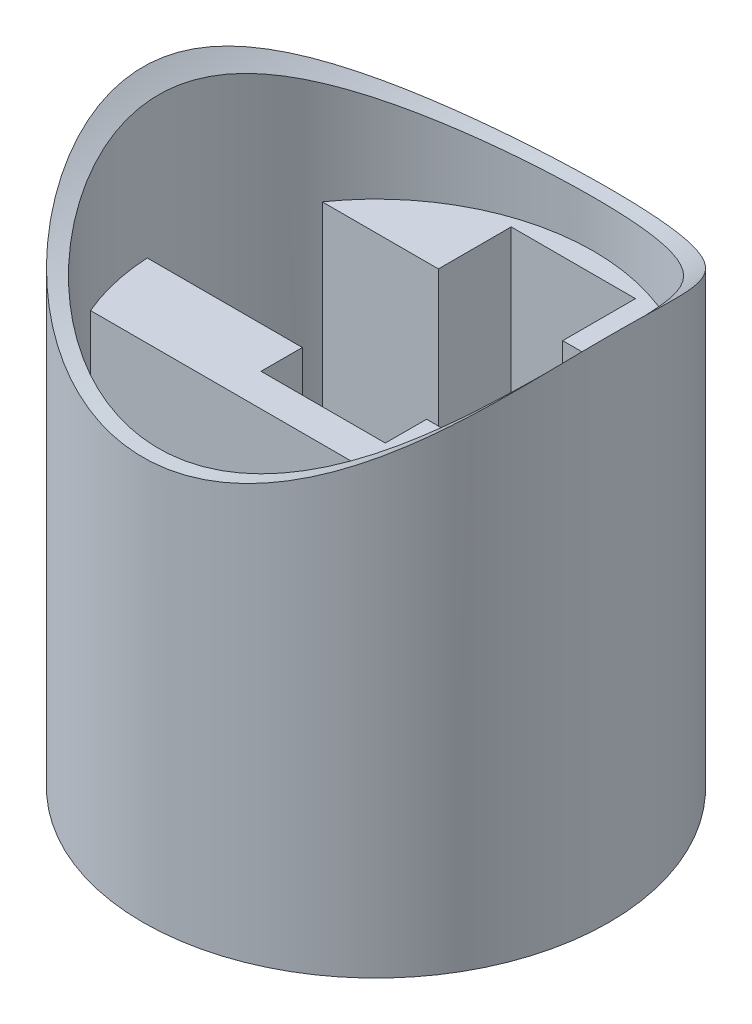
SolidWorks part; units mm, degrees
ref_plane "Front Plane" through (0, 0, 0) normal (0, 0, 1) x (1, 0, 0)
ref_plane "Top Plane" through (0, 0, 0) normal (0, 1, 0) x (1, 0, 0)
ref_plane "Right Plane" through (0, 0, 0) normal (1, 0, 0) x (0, 0, -1)
sketch "Sketch2" plane through (0, 0, 0) normal (0, 1, 0) x (1, 0, 0)
  line L0 (-28.6937, 20.0417) -> (-10, 20.0417)
  line L1 (-10, 31.75) -> (10, 31.75)
  line L2 (-10, 31.75) -> (-10, -8.5)
  line L3 (-10, -8.5) -> (10, -8.5)
  line L4 (10, 31.75) -> (10, -8.5)
  line L5 (-34.9505, -1.8615) -> (-10, -1.8615)
  line L6 (-32.1853, -13.7516) -> (32.1853, -13.7516)
  line L7 (0, -55) -> (0, 55) construction
  line L8 (34.9505, -1.8615) -> (10, -1.8615)
  line L9 (28.6937, 20.0417) -> (10, 20.0417)
  circle A0 centre (0, 0) radius 37.5
  circle A1 centre (0, 0) radius 35
  point P14 (0, 0)
  point P18 (0, -13.7516)
  dimension "D1" = 75
  dimension "D6" = 70
  dimension "D2" = 40.25
  dimension "D3" = 20
  dimension "D4" = 10
  dimension "D5" = 8.5
  dimension "D7" = 20.0417
  dimension "D8" = 1.8615
  dimension "D9" = 5.2516
extrude "Boss-Extrude2" add sketch "Sketch2" along normal blind 37.3 contours A0 A1 | L9 A1 L0 L2 L1 L4 | L6 A1 L8 L4 L3 L2 L5
sketch "Sketch3" plane through (0, 0, 0) normal (0, -1, 0) x (1, 0, 0)
  circle A0 centre (0, 0) radius 37.5
extrude "Boss-Extrude3" add sketch "Sketch3" along normal blind 20
sketch "Sketch4" plane through (0, 37.3, 0) normal (0, 1, 0) x (1, 0, 0)
  circle A0 centre (0, 0) radius 37.5
  circle A1 centre (0, 0) radius 35
extrude "Boss-Extrude4" add sketch "Sketch4" along normal blind 40
sketch "Sketch5" plane through (0, 0, 0) normal (0, 0, 1) x (1, 0, 0)
  line L1 (35, 77.3) -> (-35, 77.3) construction
  circle A0 centre (0, 94.8) radius 50
  point P6 (0, 0)
  dimension "D1" = 100
  dimension "D2" = 17.5
extrude "Cut-Extrude2" cut sketch "Sketch5" against normal blind 60 and the other way blind 60 contours A0
